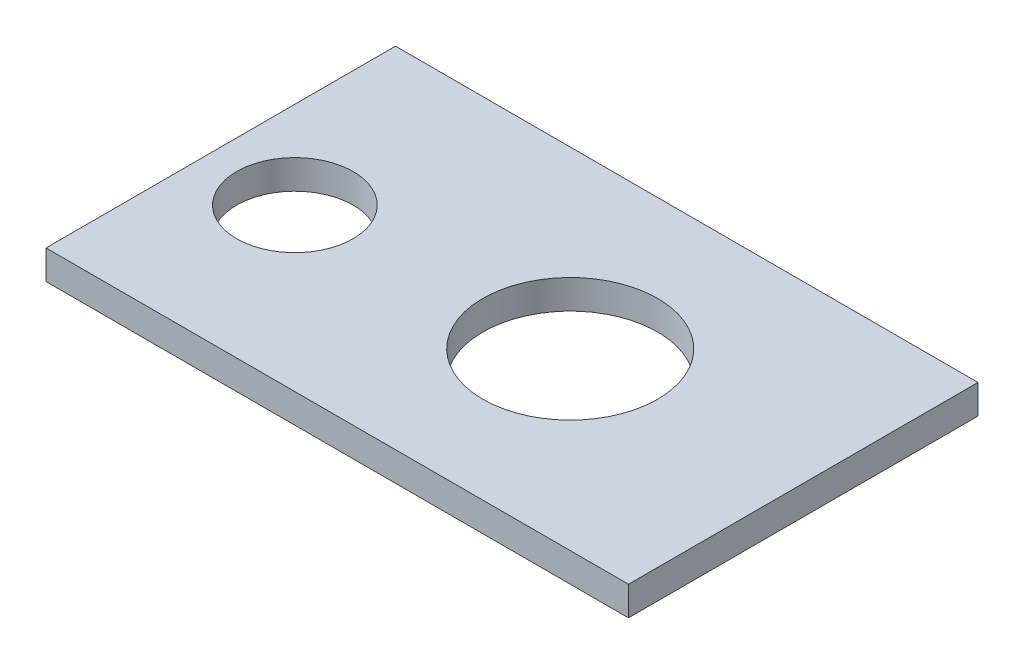
SolidWorks part; units mm, degrees
ref_plane "Front Plane" through (0, 0, 0) normal (0, 0, 1) x (1, 0, 0)
ref_plane "Top Plane" through (0, 0, 0) normal (0, 1, 0) x (1, 0, 0)
ref_plane "Right Plane" through (0, 0, 0) normal (1, 0, 0) x (0, 0, -1)
sketch "Sketch1" plane through (0, 0, 0) normal (0, 1, 0) x (1, 0, 0)
  line L0 (1000, 600) -> (0, 600)
  line L5 (0, 0) -> (1000, 0)
  line L6 (1000, 0) -> (1000, 600)
  line L7 (0, 600) -> (0, 0)
  dimension "D3" = 1000
  dimension "D4" = 600
extrude "Boss-Extrude1" add sketch "Sketch1" along normal blind 50
sketch "Sketch2" plane through (0, 50, 0) normal (0, 1, 0) x (1, 0, 0)
  line L1 (0, 0) -> (1000, 0) construction
  line L2 (0, 600) -> (0, 0) construction
  line L3 (1000, 0) -> (1000, 600) construction
  circle A0 centre (150, 277.2588) radius 100
  circle A1 centre (600, 300) radius 150
  dimension "D5" = 300
  dimension "D6" = 200
  dimension "D1" = 300
  dimension "D2" = 150
  dimension "D3" = 400
  dimension "D4" = 450.5743
extrude "Cut-Extrude1" cut sketch "Sketch2" against normal through all
